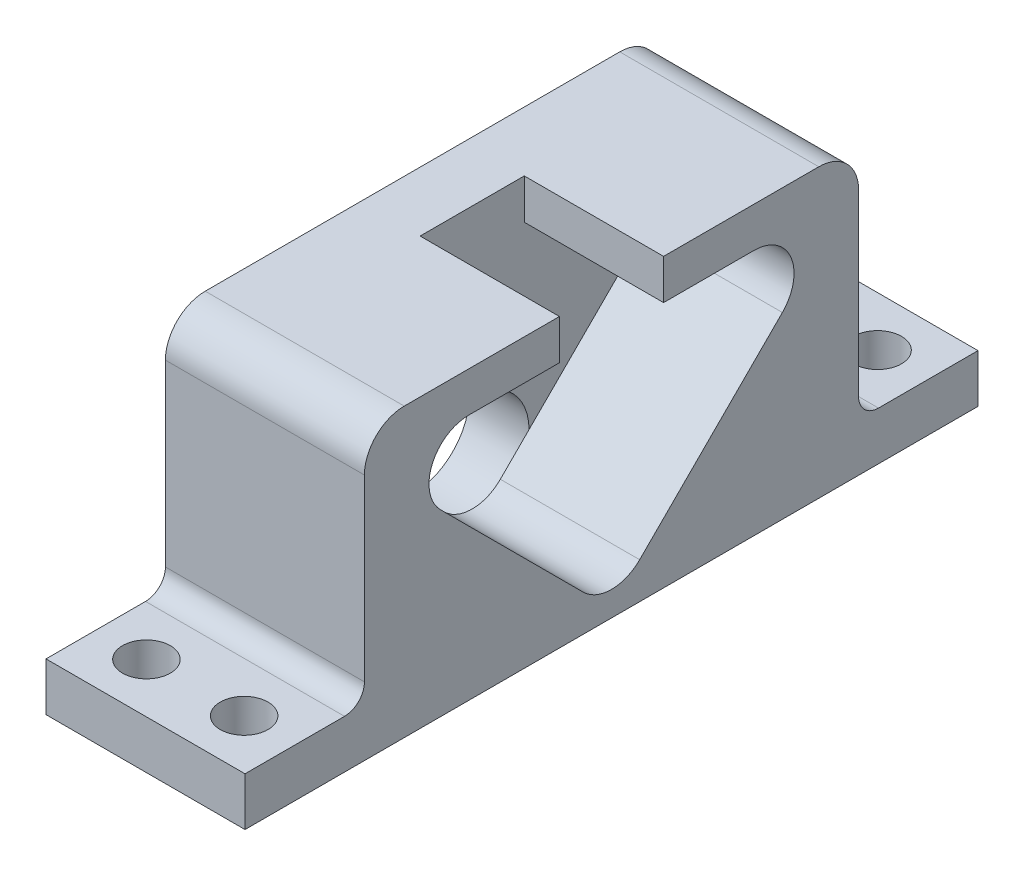
SolidWorks part; units mm, degrees
ref_plane "Front Plane" through (0, 0, 0) normal (0, 0, 1) x (1, 0, 0)
ref_plane "Top Plane" through (0, 0, 0) normal (0, 1, 0) x (1, 0, 0)
ref_plane "Right Plane" through (0, 0, 0) normal (1, 0, 0) x (0, 0, -1)
sketch "Sketch1" plane through (0, 0, 0) normal (1, 0, 0) x (0, 0, -1)
  line L0 (0, 0) -> (50, 50)
  line L1 (50, 50) -> (-50, 50)
  line L2 (-50, 50) -> (0, 0)
sketch "Sketch2" plane through (0, 0, 0) normal (1, 0, 0) x (0, 0, -1)
  line L0 (-62.0711, 55) -> (-62.0711, -5)
  line L1 (62.0711, 55) -> (-62.0711, 55)
  line L2 (-62.0711, -5) -> (-92.0711, -5)
  line L5 (50, 50) -> (-50, 50) construction
  line L6 (-92.0711, -5) -> (-92.0711, -17.1362)
  line L7 (-92.0711, -17.1362) -> (92.0711, -17.1362)
  line L8 (92.0711, -17.1362) -> (92.0711, -5)
  line L9 (92.0711, -5) -> (62.0711, -5)
  line L10 (62.0711, -5) -> (62.0711, 55)
  dimension "D1" = 30
  dimension "D3" = 5
  dimension "D4" = 60
extrude "Boss-Extrude2" add sketch "Sketch2" along normal mid plane 50
sketch "Sketch3" plane through (25, 0, 0) normal (1, 0, 0) x (0, 0, -1)
  line L0 (0, -15.0663) -> (60, 44.9337)
  line L1 (60, 44.9337) -> (-60, 44.9337)
  line L2 (-60, 44.9337) -> (0, -15.0663)
extrude "Cut-Extrude2" cut sketch "Sketch3" against normal blind 35
fillet "Fillet3" radius 10 3 edges at (7.5, -15.0663, 0) (7.5, 44.9337, -60) (7.5, 44.9337, 60)
sketch "Sketch5" plane through (-10, 0, 0) normal (1, 0, 0) x (0, 0, -1)
  circle A0 centre (0, -0.9242) radius 14.2948
  point P3 (0, -0.9242)
extrude "Cut-Extrude3" cut sketch "Sketch5" against normal up to surface (15 mm away) up to face at (-25, 6.9659, 0)
fillet "Fillet4" radius 10 2 edges at (0, 55, -62.0711) (0, 55, 62.0711)
fillet "Fillet5" radius 5 2 edges at (0, -5, -62.0711) (0, -5, 62.0711)
sketch "Sketch6" plane through (0, -5, 0) normal (0, 1, 0) x (1, 0, 0)
  line L0 (-25, -79.5711) -> (25, -79.5711) construction
  line L1 (-25, -67.0711) -> (-25, -92.0711) construction
  line L2 (25, -67.0711) -> (25, -92.0711) construction
  line L3 (0, -67.0711) -> (0, -92.0711) construction
  line L4 (25, -67.0711) -> (-25, -67.0711) construction
  line L5 (25, -92.0711) -> (-25, -92.0711) construction
  circle A0 centre (-12.2731, -79.5711) radius 6
  circle A1 centre (12.2731, -79.5711) radius 6
extrude "Cut-Extrude4" cut sketch "Sketch6" against normal blind 35
mirror "Mirror1" about plane through (0, 0, 0) normal (0, 0, 1) of "Cut-Extrude4"
sketch "Sketch8" plane through (0, 55, 0) normal (0, 1, 0) x (1, 0, 0)
  line L1 (25, -13.0831) -> (-10, -13.0831)
  line L2 (25, -13.0831) -> (25, 13.0831)
  line L3 (25, 13.0831) -> (-10, 13.0831)
  line L7 (-10, 35.8579) -> (-10, -35.8579) construction
  line L8 (-10, 13.0831) -> (-10, -13.0831)
  point P0 (0, 0)
extrude "Cut-Extrude6" cut sketch "Sketch8" against normal up to surface (10.0663 mm away) up to face at (7.5, 44.9337, 0)
scale "Scale1" scale about centroid uniform scaling yes scale factor 0.25
sketch "Sketch10" plane through (0, 21.6998, 0) normal (0, -1, 0) x (-1, 0, 0)
  line L0 (-4.5483, -8.9645) -> (-4.5483, 8.9645) construction
